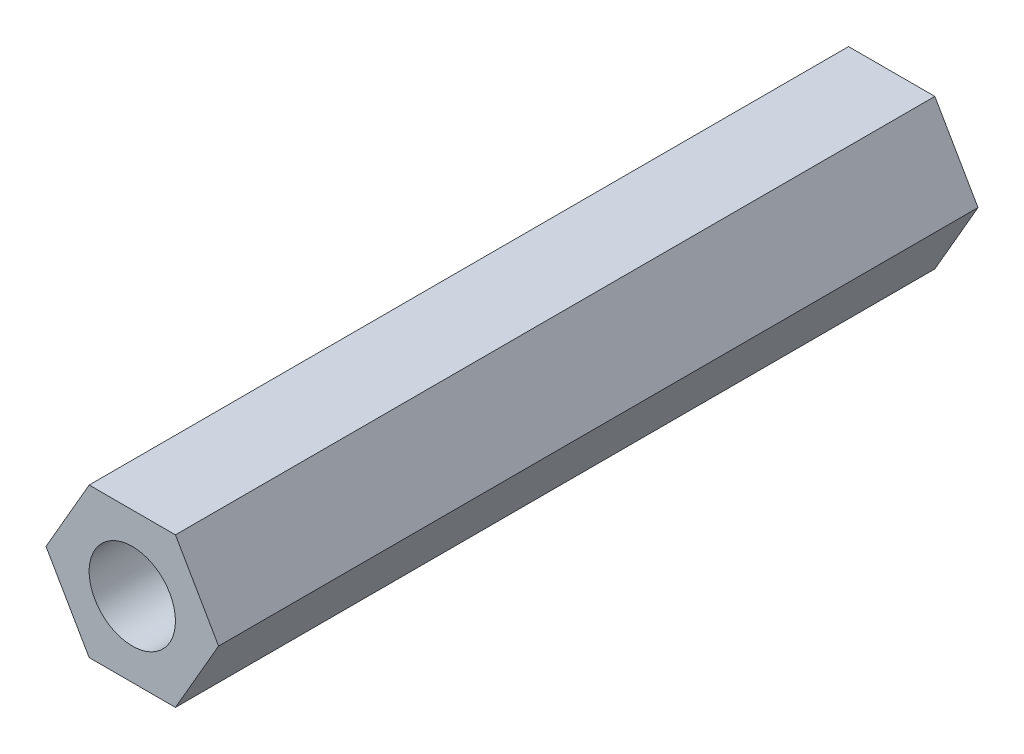
SolidWorks part; units mm, degrees
material "普通碳钢"
ref_plane "前视" through (0, 0, 0) normal (0, 0, 1) x (1, 0, 0)
ref_plane "上视" through (0, 0, 0) normal (0, 1, 0) x (1, 0, 0)
ref_plane "右视" through (0, 0, 0) normal (1, 0, 0) x (0, 0, -1)
sketch "草图1" plane through (0, 0, 0) normal (0, 0, 1) x (1, 0, 0)
  line L0 (0, 0) -> (2.5, 0)
  line L1 (2.5, 0) -> (3.75, -2.1651)
  line L2 (3.75, -2.1651) -> (2.5, -4.3301)
  line L3 (2.5, -4.3301) -> (0, -4.3301)
  line L4 (0, -4.3301) -> (-1.25, -2.1651)
  line L5 (-1.25, -2.1651) -> (0, 0)
  dimension "D1" = 5
  dimension "D2" = 5
extrude "凸台-拉伸1" add sketch "草图1" along normal blind 22
hole_wizard "M3 螺纹孔1" positions "草图3" profile "草图2" tap size "M3" standard "GB" end condition through all
sketch "草图3" plane through (0, 0, 22) normal (0, 0, 1) x (1, 0, 0)
  line L0 (-1.25, -2.1651) -> (3.75, -2.1651) construction
  line L2 (1.25, 0) -> (1.25, -4.3301) construction
  line L3 (2.5, 0) -> (0, 0) construction
  line L4 (0, -4.3301) -> (2.5, -4.3301) construction
  point P0 (1.25, -2.1651)
cosmetic thread "孔螺蚊线1" parameters "D2"=3
sketch "草图2" plane through (1.25, -2.1651, 22) normal (1, 0, 0) x (0, -1, 0)
  line L0 (0, 0) -> (0, 22)
  line L1 (0, 22) -> (1.25, 22)
  line L2 (1.25, 22) -> (1.25, 0)
  line L5 (1.25, 0) -> (0, 0)
  line L11 (0, -6.35) -> (0, 107.95) construction
  dimension "通孔螺纹孔钻头直径" = 2.5
  dimension "通孔螺纹孔钻头深度" = 22
